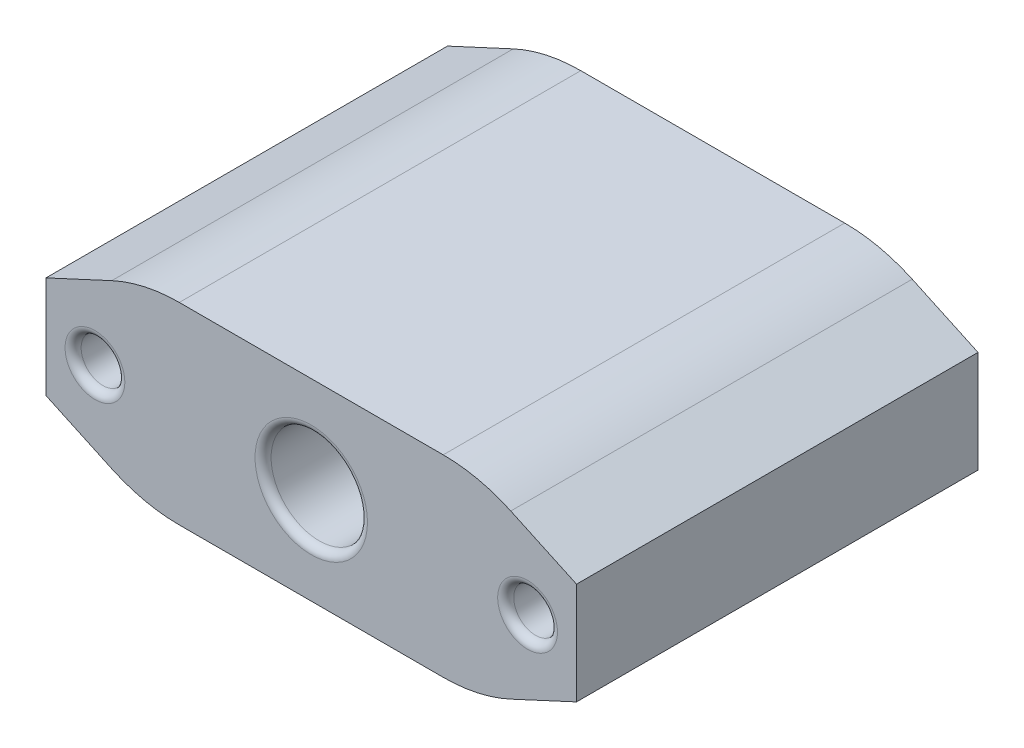
SolidWorks part; units mm, degrees
ref_plane "Front Plane" through (0, 0, 0) normal (0, 0, 1) x (1, 0, 0)
ref_plane "Top Plane" through (0, 0, 0) normal (0, 1, 0) x (1, 0, 0)
ref_plane "Right Plane" through (0, 0, 0) normal (1, 0, 0) x (0, 0, -1)
sketch "Sketch1" plane through (0, 0, 0) normal (0, 0, 1) x (-1, 0, 0)
  line L27 (16.518, 3.175) -> (16.518, -3.175)
  line L28 (10.422, -3.175) -> (10.422, 3.175) construction
  line L29 (16.518, -3.175) -> (10.422, -3.175) construction
  line L30 (16.518, 3.175) -> (10.422, 3.175) construction
  line L31 (10.422, -3.175) -> (10.422, -6) construction
  line L32 (10.422, -3.175) -> (16.518, 3.175) construction
  line L33 (10.422, 3.175) -> (16.518, -3.175) construction
  line L34 (0, -6) -> (0, 6) construction
  line L35 (10.422, -6) -> (-10.422, -6)
  line L36 (10.422, 3.175) -> (10.422, 6) construction
  line L37 (10.422, 6) -> (-10.422, 6)
  line L38 (-13.47, 0) -> (13.47, 0) construction
  line L39 (16.518, -3.175) -> (10.422, -6)
  line L40 (16.518, 3.175) -> (10.422, 6)
  line L41 (-16.518, -3.175) -> (-10.422, -3.175) construction
  line L42 (-10.422, -3.175) -> (-10.422, 3.175) construction
  line L43 (-10.422, -3.175) -> (-16.518, 3.175) construction
  line L44 (-10.422, 3.175) -> (-16.518, -3.175) construction
  line L45 (-16.518, 3.175) -> (-10.422, 3.175) construction
  line L46 (-10.422, 3.175) -> (-10.422, 6) construction
  line L47 (-10.422, -3.175) -> (-10.422, -6) construction
  line L48 (-16.518, 3.175) -> (-16.518, -3.175)
  line L49 (-16.518, 3.175) -> (-10.422, 6)
  line L50 (-16.518, -3.175) -> (-10.422, -6)
  circle A3 centre (13.47, 0) radius 1.3609
  circle A4 centre (-13.47, 0) radius 1.3609
  circle A5 centre (0, 0) radius 3
  point P3 (0, 0)
  point P5 (10.422, 3.175)
  point P10 (10.422, -6)
  point P11 (13.47, 0)
  point P44 (0, 0)
  point P46 (0, 0)
  dimension "D7" = 6
  dimension "D8" = 2.7219
  dimension "D9" = 20.8439
  dimension "D5" = 33.0359
  dimension "D6" = 12
  dimension "D10" = 6.35
extrude "Boss-Extrude1" add sketch "Sketch1" along normal blind 25
fillet "Fillet1" radius 10 1 edges at (-10.422, 6, 12.5)
fillet "Fillet2" radius 10 1 edges at (-10.422, -6, 12.5)
fillet "Fillet4" radius 10 1 edges at (10.422, -6, 12.5)
fillet "Fillet5" radius 10 1 edges at (10.422, 6, 12.5)
fillet "Fillet8" radius 0.5 1 edges at (3, 0, 0)
fillet "Fillet9" radius 0.5 1 edges at (12.109, 0, 0)
fillet "Fillet10" radius 0.5 1 edges at (-12.109, 0, 0)
fillet "Fillet11" radius 0.5 1 edges at (3, 0, 25)
fillet "Fillet12" radius 0.5 1 edges at (12.109, 0, 25)
fillet "Fillet13" radius 0.5 1 edges at (-12.109, 0, 25)
